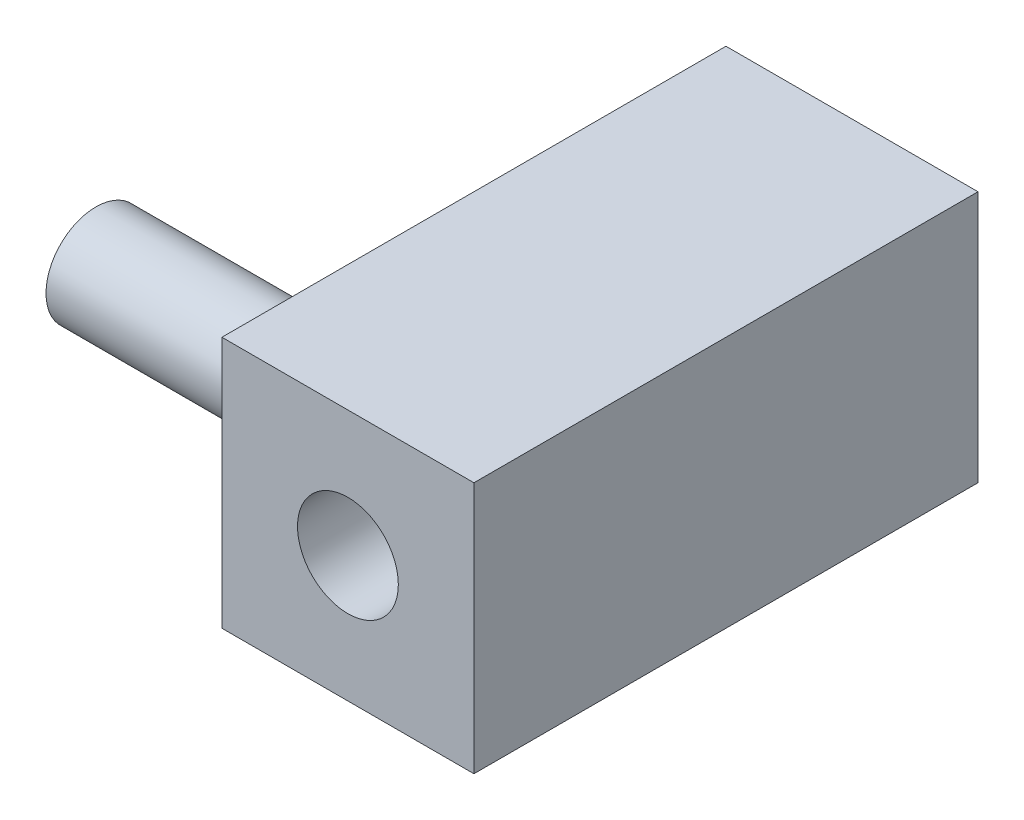
SolidWorks part; units mm, degrees
ref_plane "Front Plane" through (0, 0, 0) normal (0, 0, 1) x (1, 0, 0)
ref_plane "Top Plane" through (0, 0, 0) normal (0, 1, 0) x (1, 0, 0)
ref_plane "Right Plane" through (0, 0, 0) normal (1, 0, 0) x (0, 0, -1)
sketch "Sketch1" plane through (0, 0, 0) normal (0, 0, 1) x (1, 0, 0)
  line L1 (0, 0) -> (-50, 0)
  line L2 (0, 0) -> (0, 50)
  line L3 (0, 50) -> (-50, 50)
  line L4 (-50, 0) -> (-50, 50)
  dimension "D1" = 50
  dimension "D2" = 50
extrude "Boss-Extrude1" add sketch "Sketch1" along normal blind 100
sketch "Sketch2" plane through (-50, 0, 0) normal (-1, 0, 0) x (0, 0, 1)
  line L0 (100, 50) -> (100, 0) construction
  line L1 (100, 50) -> (0, 50) construction
  circle A0 centre (75, 25) radius 9.9
  dimension "D1" = 19.8
  dimension "D2" = 25
  dimension "D3" = 25
extrude "Boss-Extrude2" add sketch "Sketch2" along normal blind 50 contours A0
sketch "Sketch3" plane through (0, 0, 100) normal (0, 0, 1) x (1, 0, 0)
  line L0 (0, 50) -> (-50, 50) construction
  line L1 (0, 0) -> (0, 50) construction
  circle A0 centre (-25, 25) radius 10
  dimension "D1" = 20
  dimension "D2" = 25
  dimension "D3" = 25
extrude "Cut-Extrude1" cut sketch "Sketch3" against normal blind 50
